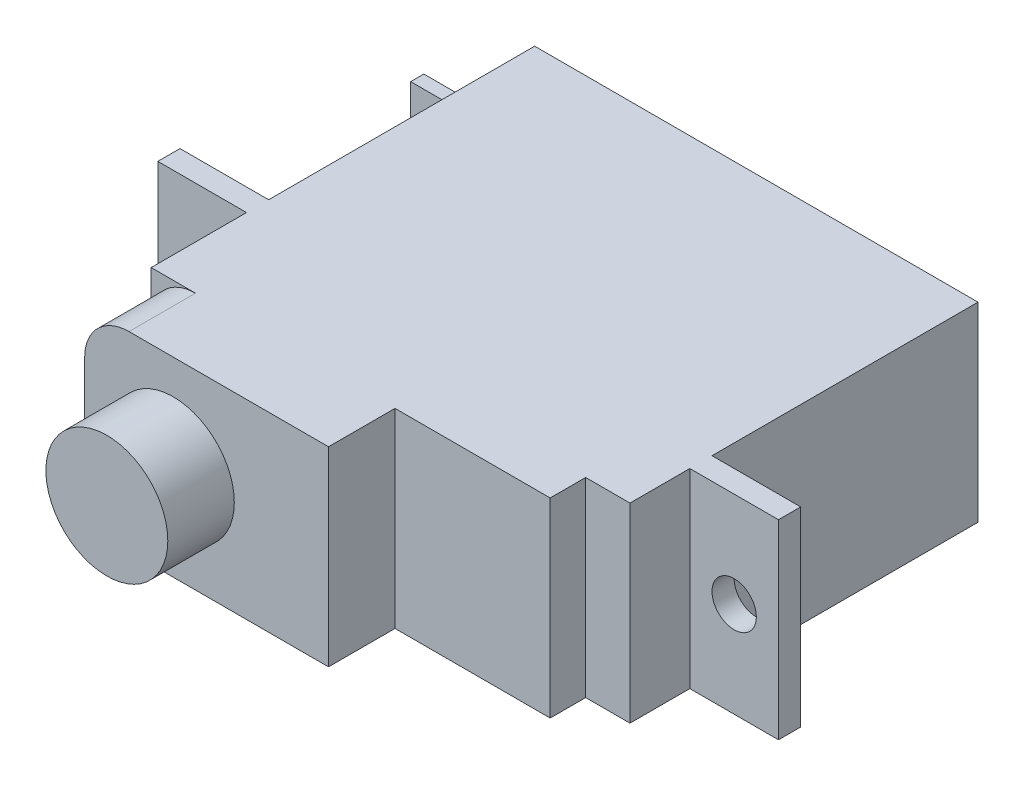
SolidWorks part; units mm, degrees
ref_plane "Front" through (0, 0, 0) normal (0, 0, 1) x (1, 0, 0)
ref_plane "Top" through (0, 0, 0) normal (0, 1, 0) x (1, 0, 0)
ref_plane "Right" through (0, 0, 0) normal (1, 0, 0) x (0, 0, -1)
sketch "Sketch2" plane through (0, 0, 0) normal (0, 0, 1) x (1, 0, 0)
  line L1 (-10, 4.3) -> (10, 4.3)
  line L2 (-10, 4.3) -> (-10, -4.3)
  line L3 (-10, -4.3) -> (10, -4.3)
  line L4 (10, 4.3) -> (10, -4.3)
  line L5 (-10, 4.3) -> (10, -4.3) construction
  line L6 (-10, -4.3) -> (10, 4.3) construction
  point P0 (0, 0)
  dimension "D1" = 20
  dimension "D2" = 8.6
extrude "Boss-Extrude1" add sketch "Sketch2" along normal blind 12
sketch "Sketch3" plane through (0, 0, 12) normal (0, 0, 1) x (1, 0, 0)
  line L1 (-14, 4.3) -> (14, 4.3)
  line L2 (-14, 4.3) -> (-14, -4.3)
  line L3 (-14, -4.3) -> (14, -4.3)
  line L4 (14, 4.3) -> (14, -4.3)
  line L5 (-14, 4.3) -> (14, -4.3) construction
  line L6 (-14, -4.3) -> (14, 4.3) construction
  line L7 (-10, -4.3) -> (10, -4.3) construction
  line L8 (14, 0) -> (-14, 0) construction
  circle A0 centre (12, 0) radius 1
  circle A1 centre (-12, 0) radius 1
  point P0 (0, 0)
  point P12 (14, 0)
  dimension "D2" = 2
  dimension "D1" = 28
  dimension "D3" = 2
  dimension "D4" = 2
extrude "Boss-Extrude2" add sketch "Sketch3" along normal blind 1
sketch "Sketch4" plane through (0, 0, 13) normal (0, 0, 1) x (1, 0, 0)
  line L0 (-14, -4.3) -> (14, -4.3) construction
  line L1 (-10, 4.3) -> (10, 4.3)
  line L2 (-10, 4.3) -> (-10, -4.3)
  line L3 (-10, -4.3) -> (10, -4.3)
  line L4 (10, 4.3) -> (10, -4.3)
  line L5 (-10, 4.3) -> (10, -4.3) construction
  line L6 (-10, -4.3) -> (10, 4.3) construction
  line L7 (-10, 4.3) -> (-10, -4.3) construction
  point P0 (0, 0)
extrude "Boss-Extrude3" add sketch "Sketch4" along normal blind 2.7
sketch "Sketch5" plane through (0, 0, 15.7) normal (0, 0, 1) x (1, 0, 0)
  line L0 (-10, -4.3) -> (10, -4.3) construction
  line L1 (-10, 4.3) -> (8, 4.3)
  line L2 (-10, 4.3) -> (-10, -4.3)
  line L3 (-10, -4.3) -> (8, -4.3)
  line L4 (8, 4.3) -> (8, -4.3)
  line L5 (-10, 4.3) -> (-10, -4.3) construction
  line L6 (-10, -4.3) -> (10, -4.3) construction
  line L7 (10, 4.3) -> (-10, 4.3) construction
  dimension "D1" = 18
extrude "Boss-Extrude4" add sketch "Sketch5" along normal blind 1.6
sketch "Sketch6" plane through (0, 0, 17.3) normal (0, 0, 1) x (1, 0, 0)
  line L0 (-10, -4.3) -> (8, -4.3) construction
  line L3 (-8, 4.3) -> (1, 4.3)
  line L4 (-10, 2.3) -> (-10, -2.3)
  line L5 (-8, -4.3) -> (1, -4.3)
  line L6 (1, 4.3) -> (1, -4.3)
  arc A0 (-10, -2.3) -> (-8, -4.3) centre (-8, -2.3) ccw
  arc A1 (-8, 4.3) -> (-10, 2.3) centre (-8, 2.3) ccw
  point P11 (-10, 4.3)
  dimension "D2" = 2
  dimension "D1" = 11
extrude "Boss-Extrude5" add sketch "Sketch6" along normal blind 3
sketch "Sketch7" plane through (0, 0, 20.3) normal (0, 0, 1) x (1, 0, 0)
  line L0 (1, 0) -> (-10, 0) construction
  line L1 (1, -4.3) -> (1, 4.3) construction
  line L2 (-10, 4.3) -> (-10, -4.3) construction
  circle A0 centre (-6, 0) radius 2.75
  dimension "D1" = 4
  dimension "D2" = 5.5
extrude "Boss-Extrude6" add sketch "Sketch7" along normal blind 3
sketch "Sketch8" plane through (-10, 0, 0) normal (-1, 0, 0) x (0, 0, 1)
  line L5 (-0.203, -0.3878) -> (4.0632, -0.3878) construction
  line L6 (0, 4.3) -> (0, -4.3) construction
  line L7 (0.5939, 0.7122) -> (0, 0.7122)
  line L8 (0.5939, 0.7122) -> (0.5939, -1.4878)
  line L9 (0.5939, -1.4878) -> (0, -1.4878)
  line L10 (0, 0.7122) -> (0, -1.4878)
  line L11 (0.5939, 0.7122) -> (0, -1.4878) construction
  line L12 (0.5939, -1.4878) -> (0, 0.7122) construction
  point P0 (0.297, -0.3878)
  point P8 (0.297, -0.3878)
  point P10 (0, 0)
  dimension "D1" = 0.5
  dimension "D2" = 1.1
extrude "Boss-Extrude7" add sketch "Sketch8" along normal blind 5
